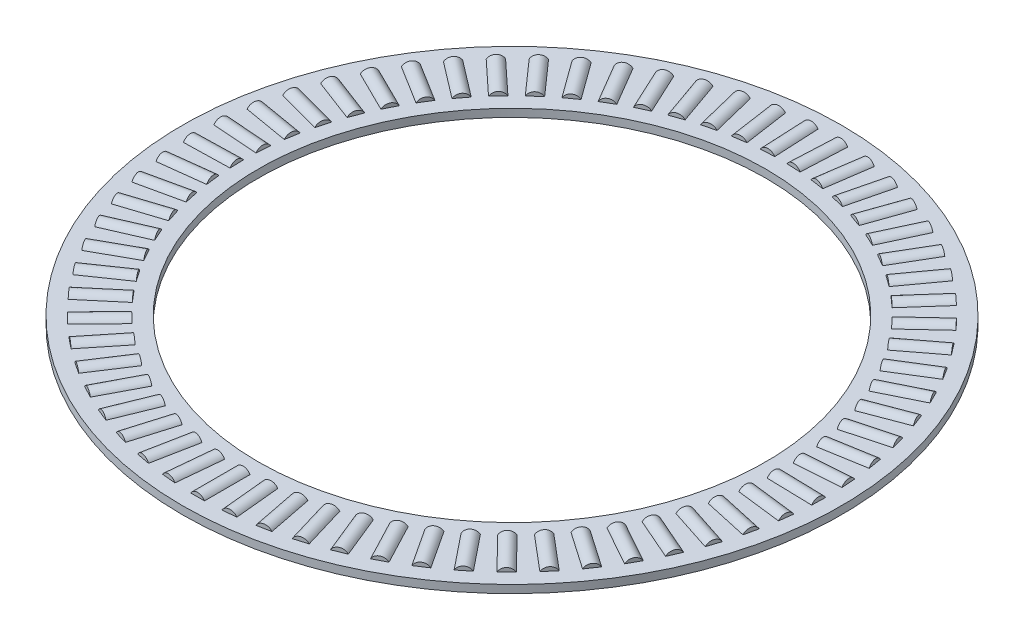
SolidWorks part; units mm, degrees
ref_plane "Front Plane" through (0, 0, 0) normal (0, 0, 1) x (1, 0, 0)
ref_plane "Top Plane" through (0, 0, 0) normal (0, 1, 0) x (1, 0, 0)
ref_plane "Right Plane" through (0, 0, 0) normal (1, 0, 0) x (0, 0, -1)
sketch "Sketch1" plane through (0, 0, 0) normal (1, 0, 0) x (0, 0, -1)
  line L0 (-41.275, 0) -> (41.275, 0) construction
  line L1 (0, -0.9922) -> (0, 0.9922) construction
  line L2 (-41.275, 0.4961) -> (-31.7754, 0.4961)
  line L3 (-41.275, 0.4961) -> (-41.275, -0.4961)
  line L4 (-41.275, -0.4961) -> (-31.7754, -0.4961)
  line L5 (-31.7754, 0.4961) -> (-31.7754, -0.4961)
  line L7 (-36.5252, 0.9922) -> (-36.5252, 0.4961) construction
  line L8 (-39.3751, 0.9922) -> (-33.6753, 0.9922) construction
  line L9 (-39.3751, 0.9922) -> (-39.3751, -0.9922) construction
  line L10 (-39.3751, -0.9922) -> (-33.6753, -0.9922) construction
  line L11 (-33.6753, 0.9922) -> (-33.6753, -0.9922) construction
  line L12 (41.275, 0.9922) -> (41.275, -0.9922) construction
  point P16 (-39.3751, 0)
  point P21 (41.275, 0)
  dimension "OD" = 82.55
  dimension "ID" = 63.5508
  dimension "Washer Thickness" = 0.9922
  dimension "D1" = 5.6998
  dimension "Thickness" = 1.9844
sketch "Sketch6" plane through (0, 0, 0) normal (0, 1, 0) x (1, 0, 0)
  circle A0 centre (0, 0) radius 41.275 construction
  circle A1 centre (0, 0) radius 31.7754 construction
  circle A2 centre (0, 0) radius 31.75 construction
  dimension "For Shaft Diameter" = 63.5
  dimension "OD" = 82.55
  dimension "ID" = 63.5508
sketch "Sketch5" plane through (0, 0, 0) normal (1, 0, 0) x (0, 0, -1)
  line L1 (-41.275, 0.4961) -> (-31.7754, 0.4961)
  line L2 (-41.275, 0.4961) -> (-41.275, -0.4961)
  line L3 (-41.275, -0.4961) -> (-31.7754, -0.4961)
  line L4 (-31.7754, 0.4961) -> (-31.7754, -0.4961)
revolve "Revolve3" add sketch "Sketch5" angle 360 about L1
sketch "Sketch3" plane through (0, 0, 0) normal (1, 0, 0) x (0, 0, -1)
  line L0 (-39.3751, 0.9922) -> (-39.3751, -0.9922) construction
  line L1 (-39.3751, 0) -> (-33.6753, 0)
  line L2 (-39.3751, 0) -> (-39.3751, 0.9922)
  line L3 (-39.3751, 0.9922) -> (-33.6753, 0.9922)
  line L4 (-33.6753, 0) -> (-33.6753, 0.9922)
revolve "Cut-Revolve1" cut sketch "Sketch3" angle 360 about L1
sketch "Sketch2" plane through (0, 0, 0) normal (1, 0, 0) x (0, 0, -1)
  line L1 (-39.3751, 0) -> (-33.6753, 0)
  line L2 (-39.3751, 0) -> (-39.3751, 0.9922)
  line L3 (-39.3751, 0.9922) -> (-33.6753, 0.9922)
  line L4 (-33.6753, 0) -> (-33.6753, 0.9922)
revolve "Revolve2" add sketch "Sketch2" angle 360 about L1
ref_axis "Axis1" through (0, 0.9922, 0) along (0, -1, 0)
pattern_circular "CirPattern1" count 65 every 5.538 about axis through (0, 0.9922, 0) along (0, -1, 0) of bodies 187 411
pattern_circular "CirPattern2" count 65 every 5.538 about axis through (0, 0, 0) along (0, 1, 0) of "Cut-Revolve1"
equation "\"Rollers@CirPattern1\"= \"OD@Sketch1\" * 20"
equation "\"Angle@CirPattern1\" = 360/\"Rollers@CirPattern1\""
equation "\"D1@CirPattern2\" = \"Rollers@CirPattern1\""
equation "\"D2@CirPattern2\" = \"Angle@CirPattern1\""
equation "\"D1@Sketch1\"=((\"OD@Sketch1\"-\"ID@Sketch1\")/2)*.6"
